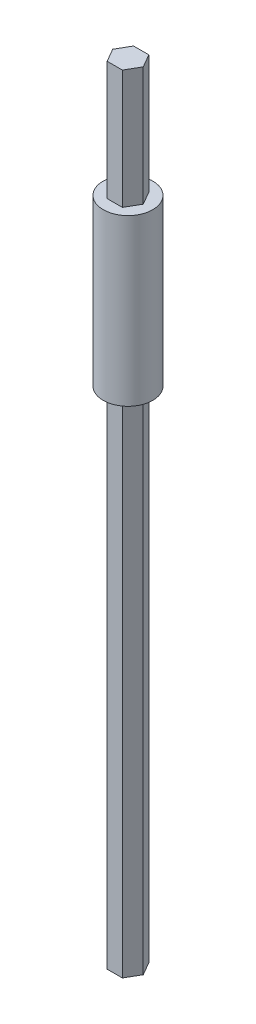
SolidWorks part; units mm, degrees
ref_plane "Alzado" through (0, 0, 0) normal (0, 0, 1) x (1, 0, 0)
ref_plane "Planta" through (0, 0, 0) normal (0, 1, 0) x (1, 0, 0)
ref_plane "Vista lateral" through (0, 0, 0) normal (1, 0, 0) x (0, 0, -1)
sketch "Croquis2" plane through (0, 71.3, 0) normal (0, 1, 0) x (1, 0, 0)
  circle A2 centre (1.5556, 1.5556) radius 3.75
extrude "Saliente-Extruir2" add sketch "Croquis2" along normal blind 25
sketch "Croquis3" plane through (0, 96.3, 0) normal (0, 1, 0) x (1, 0, 0)
  line L7 (3.865, 1.5556) -> (2.7103, 3.5556)
  line L8 (2.7103, 3.5556) -> (0.4009, 3.5556)
  line L9 (0.4009, 3.5556) -> (-0.7538, 1.5556)
  line L10 (-0.7538, 1.5556) -> (0.4009, -0.4444)
  line L11 (0.4009, -0.4444) -> (2.7103, -0.4444)
  line L12 (2.7103, -0.4444) -> (3.865, 1.5556)
  circle A2 centre (1.5556, 1.5556) radius 2 construction
extrude "Saliente-Extruir4" add sketch "Croquis3" along normal blind 18
sketch "Croquis4" plane through (0, 71.3, 0) normal (0, -1, 0) x (1, 0, 0)
  line L1 (3.865, -1.5556) -> (2.7103, 0.4444)
  line L2 (2.7103, 0.4444) -> (0.4009, 0.4444)
  line L3 (0.4009, 0.4444) -> (-0.7538, -1.5556)
  line L4 (-0.7538, -1.5556) -> (0.4009, -3.5556)
  line L5 (0.4009, -3.5556) -> (2.7103, -3.5556)
  line L6 (2.7103, -3.5556) -> (3.865, -1.5556)
  circle A0 centre (1.5556, -1.5556) radius 2 construction
extrude "Saliente-Extruir5" add sketch "Croquis4" along normal blind 76
